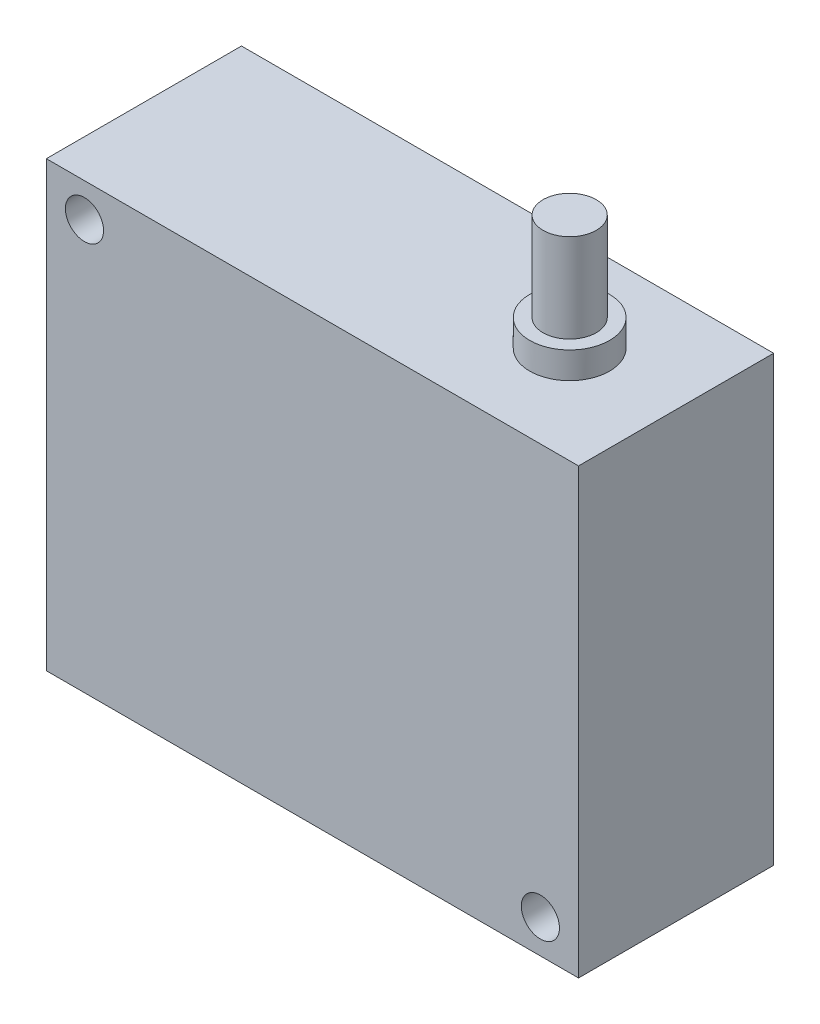
SolidWorks part; units mm, degrees
ref_plane "前视基准面" through (0, 0, 0) normal (0, 0, 1) x (1, 0, 0)
ref_plane "上视基准面" through (0, 0, 0) normal (0, 1, 0) x (1, 0, 0)
ref_plane "右视基准面" through (0, 0, 0) normal (1, 0, 0) x (0, 0, -1)
sketch "草图1" plane through (0, 0, 0) normal (0, 0, 1) x (1, 0, 0)
  line L1 (0, 0) -> (60, 0)
  line L2 (0, 0) -> (0, 50)
  line L3 (0, 50) -> (60, 50)
  line L4 (60, 0) -> (60, 50)
  dimension "D1" = 50
  dimension "D2" = 60
extrude "凸台-拉伸1" add sketch "草图1" along normal blind 22
sketch "草图2" plane through (0, 50, 0) normal (0, 1, 0) x (1, 0, 0)
  line L0 (60, -11) -> (28.0051, -11) construction
  line L1 (60, -22) -> (60, 0) construction
  circle A0 centre (48, -11) radius 4.5
  dimension "D1" = 9
  dimension "D2" = 12
extrude "凸台-拉伸2" add sketch "草图2" along normal blind 3
sketch "草图3" plane through (0, 53, 0) normal (0, 1, 0) x (1, 0, 0)
  circle A0 centre (48, -11) radius 3
  dimension "D1" = 6
extrude "凸台-拉伸3" add sketch "草图3" along normal blind 10
sketch "草图5" plane through (0, 0, 0) normal (0, -1, 0) x (1, 0, 0)
  line L0 (5, 7.5) -> (25.1759, 7.5) construction
  line L1 (5, 12.5) -> (45, 12.5)
  line L2 (5, 12.5) -> (5, 2.5)
  line L3 (5, 2.5) -> (45, 2.5)
  line L4 (45, 12.5) -> (45, 2.5)
  line L5 (0, 0) -> (60, 0) construction
  line L6 (0, 22) -> (0, 0) construction
  dimension "D1" = 7.5
  dimension "D2" = 10
  dimension "D3" = 5
  dimension "D4" = 40
sketch "草图4" plane through (0, 0, 0) normal (0, -1, 0) x (1, 0, 0)
  line L0 (0, 0) -> (60, 0) construction
  line L1 (0, 22) -> (0, 0) construction
  circle A0 centre (12.5, 7.5) radius 0.5
  dimension "D1" = 1
  dimension "D3" = 12.5
  dimension "D2" = 7.5
extrude "凸台-拉伸4" add sketch "草图4" along normal blind 5
extrude "切除-拉伸1" cut sketch "草图5" against normal blind 0.01
sketch "草图6" plane through (0, 0, 22) normal (0, 0, 1) x (1, 0, 0)
  line L0 (0, 50) -> (0, 0) construction
  line L1 (0, 0) -> (60, 0) construction
  circle A0 centre (55.7, 3.8) radius 2.15
  circle A1 centre (4.3, 46.2) radius 2.15
  dimension "D1" = 4.3
  dimension "D2" = 42.4
  dimension "D3" = 51.4
  dimension "D4" = 4.3
  dimension "D5" = 3.8
extrude "切除-拉伸2" cut sketch "草图6" against normal through all
sketch "草图7" plane through (60, 0, 0) normal (1, 0, 0) x (0, 0, -1)
  line L0 (-7.5, -5) -> (-8, -4.5)
  line L1 (-8, -5) -> (-7, -5) construction
  line L3 (-8, -4.5) -> (-8, -5)
  line L4 (-8, -5) -> (-7.5, -5)
  dimension "D1" = 45
extrude "切除-拉伸3" cut sketch "草图7" against normal through all
sketch "草图8" plane through (0, 0, 22) normal (0, 0, 1) x (1, 0, 0)
  line L0 (12.5, 0) -> (12.5, -30)
  line L1 (13, 0) -> (12, 0) construction
  line L2 (12.5, -30) -> (42, 0)
  line L3 (60, 0) -> (60, 50) construction
  line L4 (0, 0) -> (60, 0) construction
  line L5 (12.5, -5.2561) -> (36.8315, -5.2561)
  dimension "D1" = 18
  dimension "D2" = 30
